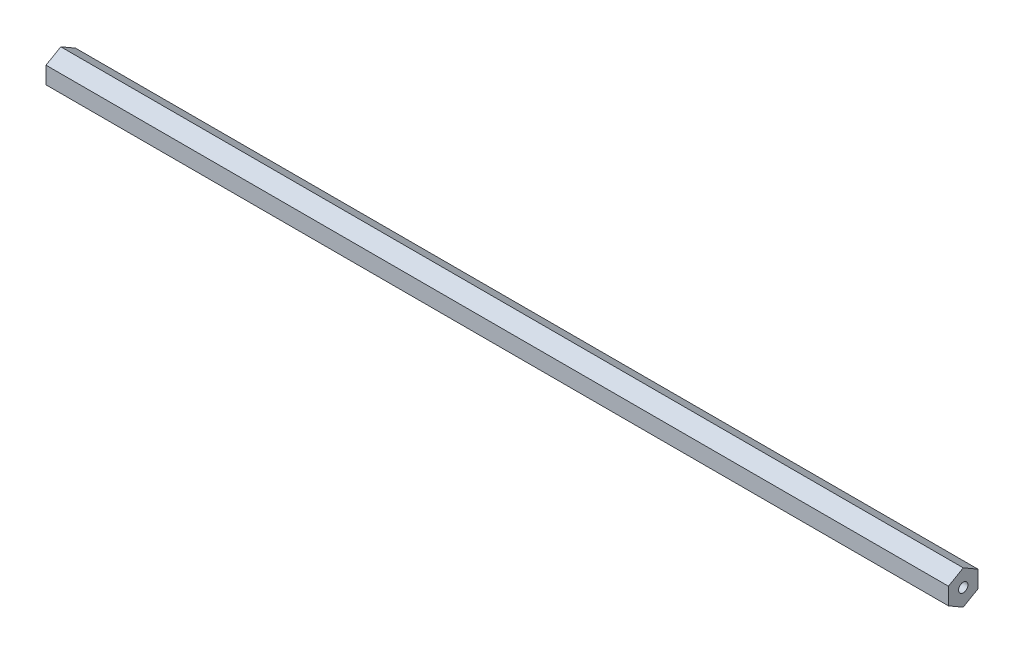
SolidWorks part; units mm, degrees
material "7075-T6 (SN)"
ref_plane "Front Plane" through (0, 0, 0) normal (0, 0, 1) x (1, 0, 0)
ref_plane "Top Plane" through (0, 0, 0) normal (0, 1, 0) x (1, 0, 0)
ref_plane "Right Plane" through (0, 0, 0) normal (1, 0, 0) x (0, 0, -1)
sketch "Sketch1" plane through (0, 0, 0) normal (1, 0, 0) x (0, 0, -1)
  line L1 (0, 7.3323) -> (-6.35, 3.6662)
  line L2 (-6.35, 3.6662) -> (-6.35, -3.6662)
  line L3 (-6.35, -3.6662) -> (0, -7.3323)
  line L4 (0, -7.3323) -> (6.35, -3.6662)
  line L5 (6.35, -3.6662) -> (6.35, 3.6662)
  line L6 (6.35, 3.6662) -> (0, 7.3323)
  circle A2 centre (0, 0) radius 6.35 construction
  dimension "D2" = 12.7
extrude "Boss-Extrude1" add sketch "Sketch1" along normal mid plane 388.1438
hole_wizard "#10-32 Tapped Hole1" positions "3DSketch1" profile "Sketch2" tap size "#10-32" standard "ANSI Inch"
sketch3d "3DSketch1"
  point P0 (194.0719, 0, 0)
  point P2 (-194.0719, 0, 0)
sketch "Sketch2" plane through (194.0719, 0, 0) normal (0, 1, 0) x (0, 0, -1)
  line L0 (0, 0) -> (0, 17.5608)
  line L1 (0, 17.5608) -> (2.0193, 16.3474)
  line L2 (2.0193, 16.3474) -> (2.0193, 0)
  line L5 (2.0193, 0) -> (0, 0)
  line L10 (0, 17.5608) -> (-2.0193, 16.3474) construction
  line L11 (0, -6.35) -> (0, 107.95) construction
  dimension "Tap Drill Dia." = 4.0386
  dimension "Tap Drill Depth" = 16.3474
  dimension "Drill Angle" = 118
cosmetic thread "Hole Thread1" parameters "D1"=13.97, "D2"=4.826
cosmetic thread "Hole Thread2" parameters "D1"=13.97, "D2"=4.826
